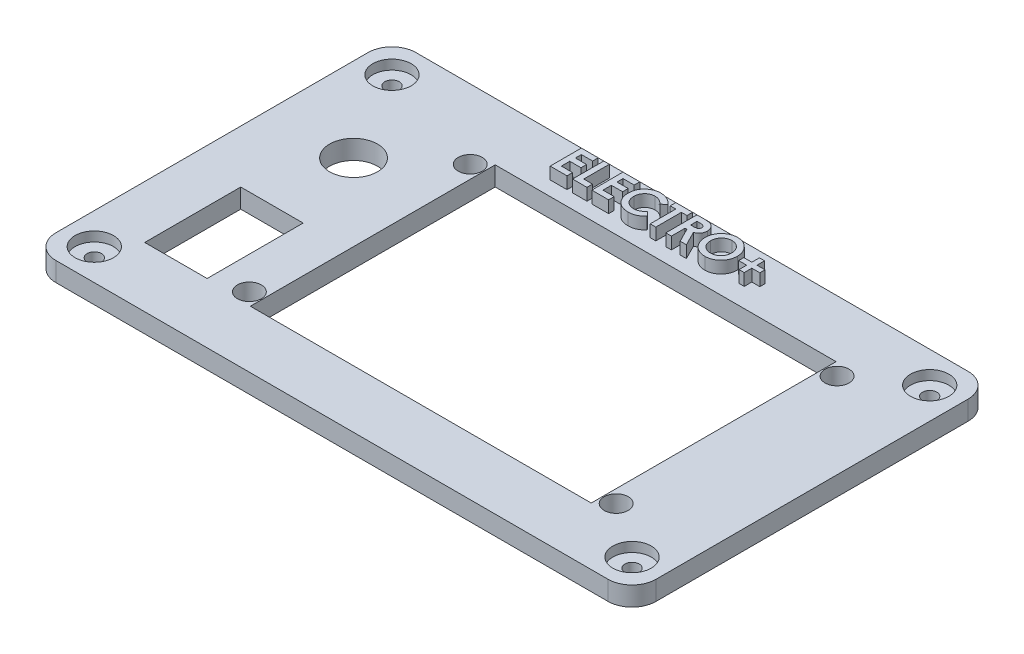
SolidWorks part; units mm, degrees
material "ABS"
ref_plane "Alzado" through (0, 0, 0) normal (0, 0, 1) x (1, 0, 0)
ref_plane "Planta" through (0, 0, 0) normal (0, 1, 0) x (1, 0, 0)
ref_plane "Vista lateral" through (0, 0, 0) normal (1, 0, 0) x (0, 0, -1)
sketch "Croquis1" plane through (0, 0, 0) normal (0, 1, 0) x (1, 0, 0)
  line L1 (-57, -32) -> (57, -32)
  line L2 (-57, -32) -> (-57, 32)
  line L3 (-57, 32) -> (57, 32)
  line L4 (57, -32) -> (57, 32)
  line L5 (-57, -32) -> (57, 32) construction
  line L6 (-57, 32) -> (57, -32) construction
  point P0 (0, 0)
  dimension "D1" = 114
  dimension "D2" = 64
extrude "Saliente-Extruir1" add sketch "Croquis1" along normal blind 5
sketch "Croquis2" plane through (0, 5, 0) normal (0, 1, 0) x (1, 0, 0)
  line L0 (57, -32) -> (57, 32) construction
  line L1 (-62.5, -37.5) -> (62.5, -37.5)
  line L2 (-62.5, -37.5) -> (-62.5, 37.5)
  line L3 (-62.5, 37.5) -> (62.5, 37.5)
  line L4 (62.5, -37.5) -> (62.5, 37.5)
  line L5 (-62.5, -37.5) -> (62.5, 37.5) construction
  line L6 (-62.5, 37.5) -> (62.5, -37.5) construction
  line L7 (57, 32) -> (-57, 32) construction
  point P0 (0, 0)
  dimension "D1" = 5.5
  dimension "D2" = 5.5
extrude "Saliente-Extruir2" add sketch "Croquis2" along normal blind 4
sketch "Croquis4" plane through (0, 0, 0) normal (0, -1, 0) x (1, 0, 0)
  line L0 (57, 32) -> (57, -32) construction
  line L1 (-29, -25.5) -> (42, -25.5)
  line L2 (-29, -25.5) -> (-29, 25.5)
  line L3 (-29, 25.5) -> (42, 25.5)
  line L4 (42, -25.5) -> (42, 25.5)
  line L5 (-29, -25.5) -> (42, 25.5) construction
  line L6 (-29, 25.5) -> (42, -25.5) construction
  line L7 (6.5, 25.5) -> (6.5, -25.5) construction
  line L8 (-29, 0) -> (42, 0) construction
  circle A0 centre (44.7, 23) radius 2.5
  circle A1 centre (-31.7, 23) radius 2.5
  circle A2 centre (44.7, -23) radius 2.5
  circle A3 centre (-31.7, -23) radius 2.5
  point P0 (6.5, 0)
  dimension "D4" = 5
  dimension "D1" = 15
  dimension "D2" = 51
  dimension "D3" = 71
  dimension "D5" = 2.5
  dimension "D6" = 2.7
extrude "Cortar-Extruir1" cut sketch "Croquis4" against normal through all contours L2 L1 L4 L3 | A1 | A3 | A2 | A0
sketch "Croquis5" plane through (0, 0, 0) normal (0, -1, 0) x (1, 0, 0)
  line L0 (-57, -32) -> (-57, 32) construction
  line L1 (57, -32) -> (-57, -32) construction
  line L2 (-29, 0) -> (-57, 0) construction
  line L3 (-29, -25.5) -> (-29, 25.5) construction
  line L5 (-51.5, 25) -> (-38.5, 25)
  line L6 (-51.5, 25) -> (-51.5, 5)
  line L7 (-51.5, 5) -> (-38.5, 5)
  line L8 (-38.5, 25) -> (-38.5, 5)
  line L9 (-51.5, 25) -> (-38.5, 5) construction
  line L10 (-51.5, 5) -> (-38.5, 25) construction
  circle A0 centre (-45, -12) radius 5
  point P10 (-45, 15)
  dimension "D1" = 10
  dimension "D3" = 20
  dimension "D2" = 12
  dimension "D4" = 13
  dimension "D5" = 20
  dimension "D6" = 5
extrude "Cortar-Extruir2" cut sketch "Croquis5" against normal through all contours A0 | L6 L5 L8 L7
sketch "Croquis10" plane through (0, 9, 0) normal (0, 1, 0) x (1, 0, 0)
sketch "Croquis12" plane through (0, 0, 0) normal (0, -1, 0) x (1, 0, 0)
  line L0 (-57, -32) -> (-57, 32) construction
  line L1 (-53, -28) -> (53, -28)
  line L2 (-53, -28) -> (-53, 28)
  line L3 (-53, 28) -> (53, 28)
  line L4 (53, -28) -> (53, 28)
  line L5 (-53, -28) -> (53, 28) construction
  line L6 (-53, 28) -> (53, -28) construction
  line L7 (57, -32) -> (-57, -32) construction
  line L8 (42, 28) -> (42, 32)
  line L9 (-57, 32) -> (57, 32) construction
  line L10 (42, 32) -> (57, 32)
  line L11 (57, 32) -> (57, -32) construction
  line L12 (57, 32) -> (57, 17)
  line L13 (57, 17) -> (53, 17)
  line L14 (53, 17) -> (53, 28)
  line L15 (0, 32) -> (0, -28) construction
  line L16 (-57, 17) -> (-53, 17)
  line L17 (-53, -28) -> (-53, 28)
  line L18 (-42, 28) -> (-42, 32)
  line L19 (-42, 32) -> (-57, 32)
  line L20 (-57, 32) -> (-57, 17)
  line L21 (0, 0) -> (53, 0) construction
  line L22 (53, 0) -> (-53, 0) construction
  line L23 (53, -17) -> (53, -28)
  line L24 (57, -17) -> (53, -17)
  line L25 (57, -32) -> (57, -17)
  line L26 (42, -32) -> (57, -32)
  line L27 (42, -28) -> (42, -32)
  line L28 (-57, -32) -> (-57, -17)
  line L29 (-42, -32) -> (-57, -32)
  line L30 (-42, -28) -> (-42, -32)
  line L31 (-57, -17) -> (-53, -17)
  line L36 (57, -32) -> (57, 32)
  line L37 (57, 32) -> (-57, 32)
  line L38 (-57, 32) -> (-57, -32)
  line L39 (-57, -32) -> (57, -32)
  line L40 (57, -32) -> (57, 32)
  line L41 (57, 32) -> (-57, 32)
  line L42 (-57, 32) -> (-57, -32)
  line L43 (-57, -32) -> (57, -32)
  point P0 (0, 0)
  circle M11 centre (-45, -12) radius 5
  line M12 (-38.5, 5) -> (-51.5, 5)
  line M13 (-51.5, 5) -> (-51.5, 25)
  line M14 (-51.5, 25) -> (-38.5, 25)
  line M15 (-38.5, 25) -> (-38.5, 5)
  circle M16 centre (44.7, 23) radius 2.5
  circle M17 centre (-31.7, 23) radius 2.5
  line M18 (57, -32) -> (57, 32)
  line M19 (57, 32) -> (-57, 32)
  line M20 (-57, 32) -> (-57, -32)
  line M21 (-57, -32) -> (57, -32)
  line M22 (-29, -25.5) -> (-29, 25.5)
  line M23 (-29, 25.5) -> (42, 25.5)
  line M24 (42, 25.5) -> (42, -25.5)
  line M25 (42, -25.5) -> (-29, -25.5)
  circle M26 centre (-31.7, -23) radius 2.5
  circle M27 centre (44.7, -23) radius 2.5
  dimension "D1" = 4
  dimension "D2" = 4
  dimension "D3" = 15
  dimension "D4" = 15
  dimension "D5" = 0
extrude "Cortar-Extruir3" cut sketch "Croquis12" against normal up to surface (5 mm away) contours L18 L3 L8 M19 | L31 L17 L16 M20 | L1 L30 L27 M21 | L24 L13 L4 M18 | L1 L4 L3 L2 L17 M11 M17 M25 M22 M23 M24 M26 M27 M16 M15 M12 M13 M14 | L13 L8 L3 L4 M18 M19 | L1 L27 L24 L4 M21 M18 | L31 L30 L1 L2 M20 M21 | L3 L18 L16 L2 M19 M20 up to face at (0, 5, 0)
sketch "Croquis13" plane through (0, 9, 0) normal (0, 1, 0) x (1, 0, 0)
  line L0 (0, -37.5) -> (0, 37.5) construction
  line L1 (-62.5, -37.5) -> (62.5, -37.5) construction
  line L2 (62.5, 37.5) -> (-62.5, 37.5) construction
  line L3 (62.5, -37.5) -> (62.5, 37.5) construction
  line L4 (62.5, 0) -> (-62.5, 0) construction
  line L5 (-62.5, 37.5) -> (-62.5, -37.5) construction
  circle A0 centre (56, 31) radius 1.5
  circle A1 centre (56, -31) radius 1.5
  circle A2 centre (-56, -31) radius 1.5
  circle A3 centre (-56, 31) radius 1.5
  dimension "D1" = 3
  dimension "D3" = 6.5
  dimension "D2" = 6.5
extrude "Cortar-Extruir4" cut sketch "Croquis13" against normal blind 10
fillet "Redondeo1" radius 5 4 edges at (-62.5, 7, -37.5) (-62.5, 7, 37.5) (62.5, 7, 37.5) (62.5, 7, -37.5)
sketch "Croquis15" plane through (0, 9, 0) normal (0, 1, 0) x (1, 0, 0)
  line L0 (-56, 29.5) -> (-56, 32.5) construction
  line L1 (0, 37.5) -> (0, -37.5) construction
  line L2 (57.5, 37.5) -> (-57.5, 37.5) construction
  line L3 (-57.5, -37.5) -> (57.5, -37.5) construction
  line L4 (0, 0) -> (62.5, 0) construction
  line L5 (62.5, -32.5) -> (62.5, 32.5) construction
  line L6 (62.5, 0) -> (-62.5, 0) construction
  line L7 (-62.5, 32.5) -> (-62.5, -32.5) construction
  circle A0 centre (-56, 31) radius 1.5 construction
  circle A1 centre (-56, 31) radius 4
  circle A2 centre (56, 31) radius 4
  circle A3 centre (56, -31) radius 4
  circle A4 centre (-56, -31) radius 4
  dimension "D1" = 8
extrude "Cortar-Extruir5" cut sketch "Croquis15" against normal blind 2
sketch "Croquis16" plane through (0, 9, 0) normal (0, 1, 0) x (1, 0, 0)
  line L0 (-62.5, 32.5) -> (-62.5, -32.5) construction
  line L1 (57.5, 37.5) -> (-57.5, 37.5) construction
  text T0 "ELECTRO+" font "Century Gothic" height 6.5
  point P8 (21.0119, 28.5)
  dimension "D1" = 41.2
  dimension "D2" = 9
extrude "Saliente-Extruir3" add sketch "Croquis16" along normal blind 2.5
